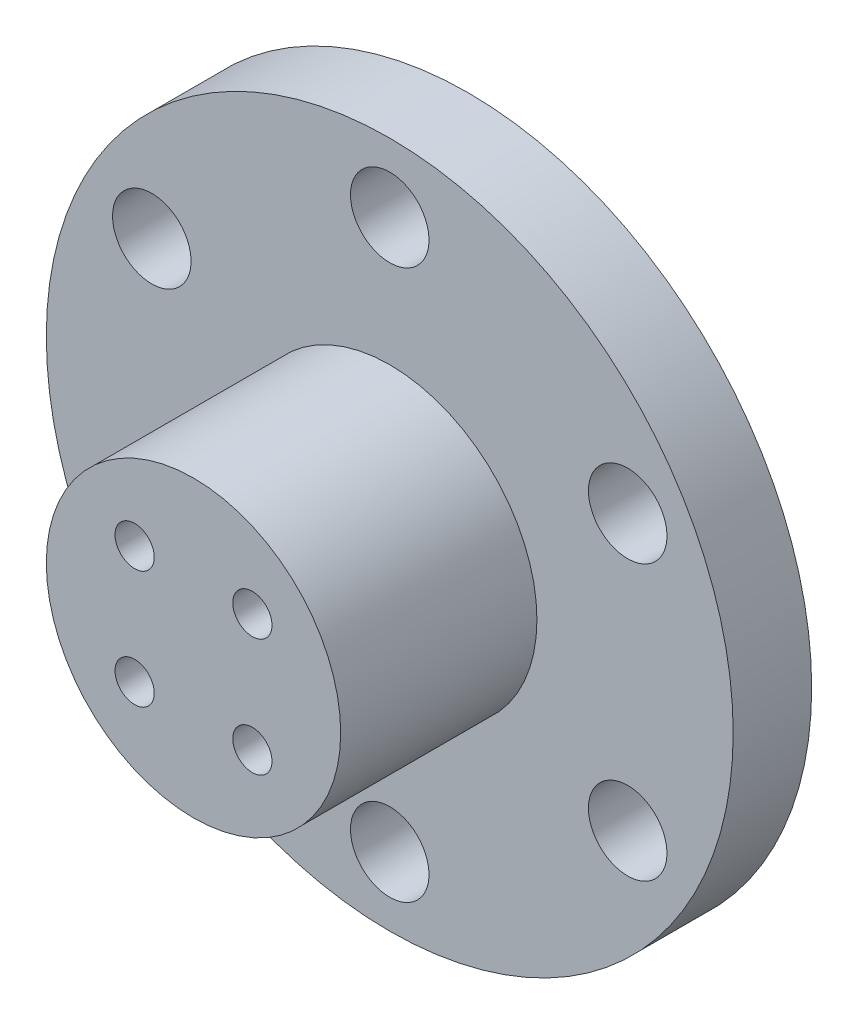
SolidWorks part; units mm, degrees
ref_plane "Front Plane" through (0, 0, 0) normal (0, 0, 1) x (1, 0, 0)
ref_plane "Top Plane" through (0, 0, 0) normal (0, 1, 0) x (1, 0, 0)
ref_plane "Right Plane" through (0, 0, 0) normal (1, 0, 0) x (0, 0, -1)
sketch "Sketch1" plane through (0, 0, 0) normal (0, 0, 1) x (1, 0, 0)
  circle A0 centre (0, 0) radius 15
  dimension "D1" = 30
extrude "Boss-Extrude1" add sketch "Sketch1" along normal blind 20
sketch "Sketch3" plane through (0, 0, 0) normal (0, 0, -1) x (-1, 0, 0)
  circle A0 centre (0, 0) radius 35
  dimension "D1" = 70
extrude "Boss-Extrude3" add sketch "Sketch3" along normal blind 8
sketch "Sketch4" plane through (0, 0, -8) normal (0, 0, -1) x (-1, 0, 0)
  circle A0 centre (0, 28) radius 4
  circle A1 centre (24.2487, 14) radius 4
  circle A2 centre (24.2487, -14) radius 4
  circle A3 centre (0, -28) radius 4
  circle A4 centre (-24.2487, -14) radius 4
  circle A5 centre (-24.2487, 14) radius 4
  point P14 (0, 0)
  dimension "D1" = 8
  dimension "D3" = 28
  dimension "D2" = 6
extrude "Cut-Extrude1" cut sketch "Sketch4" against normal blind 8
sketch "Sketch5" plane through (0, 0, -8) normal (0, 0, -1) x (-1, 0, 0)
  circle A0 centre (0, 0) radius 11
  dimension "D1" = 22
extrude "Cut-Extrude2" cut sketch "Sketch5" against normal blind 8
sketch "Sketch6" plane through (0, 0, 20) normal (0, 0, 1) x (1, 0, 0)
  line L0 (0, -15) -> (0, 15) construction
  line L1 (0, 0) -> (-15, 0) construction
  circle A0 centre (0, 0) radius 15 construction
  circle A1 centre (0, 0) radius 15 construction
  circle A2 centre (6, 6) radius 2
  circle A3 centre (-6, 6) radius 2
  circle A4 centre (6, -6) radius 2
  circle A5 centre (-6, -6) radius 2
  dimension "D3" = 4
  dimension "D1" = 6
  dimension "D2" = 6
extrude "Cut-Extrude3" cut sketch "Sketch6" against normal blind 15
fillet "Fillet1" radius 1 1 edges at (-11, 0, 0)
